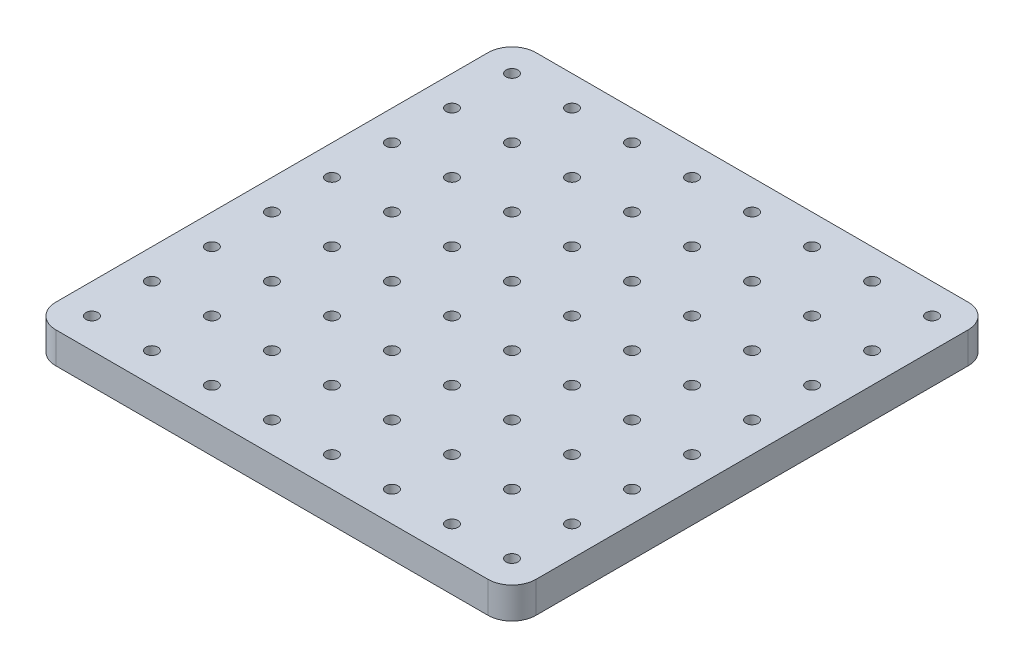
SolidWorks part; units mm, degrees
ref_plane "Front Plane" through (0, 0, 0) normal (0, 0, 1) x (1, 0, 0)
ref_plane "Top Plane" through (0, 0, 0) normal (0, 1, 0) x (1, 0, 0)
ref_plane "Right Plane" through (0, 0, 0) normal (1, 0, 0) x (0, 0, -1)
sketch "Sketch1" plane through (0, 0, 0) normal (0, 1, 0) x (1, 0, 0)
  line L1 (0, 0) -> (200, 0)
  line L2 (0, 0) -> (0, 200)
  line L3 (0, 200) -> (200, 200)
  line L4 (200, 0) -> (200, 200)
  dimension "D1" = 200
  dimension "D2" = 200
extrude "Boss-Extrude1" add sketch "Sketch1" along normal blind 13
sketch "Sketch2" plane through (0, 13, 0) normal (0, 1, 0) x (1, 0, 0)
  line L0 (100, 200) -> (100, 0) construction
  line L1 (200, 200) -> (0, 200) construction
  line L2 (0, 0) -> (200, 0) construction
  line L3 (0, 100) -> (200, 100) construction
  line L4 (0, 200) -> (0, 0) construction
  line L5 (200, 0) -> (200, 200) construction
  line L6 (10, 12.5) -> (0, 12.5) construction
  line L7 (12.5, 10) -> (12.5, 0) construction
  circle A1 centre (12.5, 12.5) radius 2.5
  dimension "D1" = 10
  dimension "D3" = 5
  dimension "D2" = 10
extrude "Cut-Extrude2" cut sketch "Sketch2" against normal blind 13
pattern_linear "LPattern1" count 8 spacing 25 along (1, 0, 0) of "Cut-Extrude2"
pattern_linear "LPattern2" count 8 spacing 25 along (0, 0, -1) of "LPattern1", "Cut-Extrude2"
fillet "Fillet1" radius 10 4 edges at (0, 6.5, 0) (0, 6.5, -200) (200, 6.5, -200) (200, 6.5, 0)
